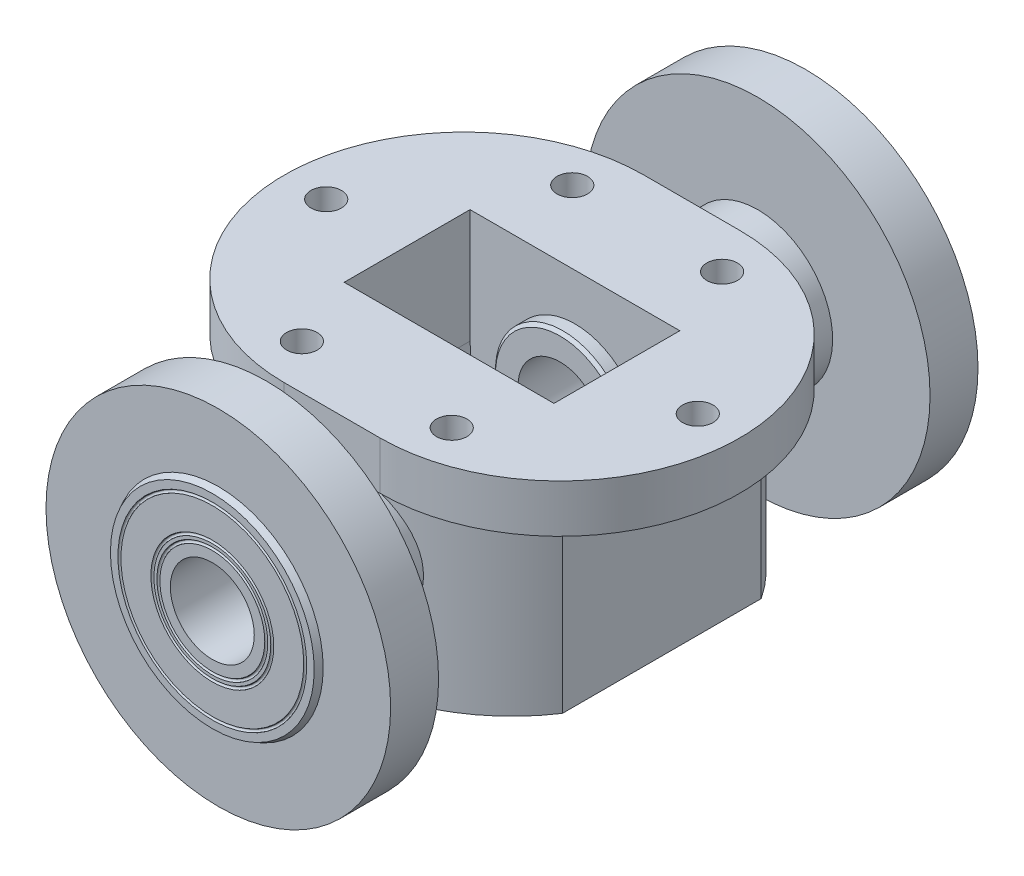
SolidWorks part; units mm, degrees
ref_plane "前视基准面" through (0, 0, 0) normal (0, 0, 1) x (1, 0, 0)
ref_plane "上视基准面" through (0, 0, 0) normal (0, 1, 0) x (1, 0, 0)
ref_plane "右视基准面" through (0, 0, 0) normal (1, 0, 0) x (0, 0, -1)
sketch "草图1" plane through (0, 0, 0) normal (0, 0, 1) x (1, 0, 0)
  circle A0 centre (0, 0) radius 57.5
  dimension "D1" = 115
extrude "凸台-拉伸1" add sketch "草图1" along normal blind 16
sketch "草图2" plane through (0, 0, 16) normal (0, 0, 1) x (1, 0, 0)
  circle A0 centre (0, 0) radius 35
  dimension "D1" = 70
ref_plane "基准面1" through (0, 0, 18) normal (0, 0, 1) x (1, 0, 0)
sketch "草图3" plane through (0, 0, 18) normal (0, 0, 1) x (1, 0, 0)
  circle A0 centre (0, 0) radius 34
  dimension "D1" = 68
loft "放样1" add profiles "草图2", "草图3"
ref_plane "基准面2" through (0, 0, -82) normal (0, 0, 1) x (1, 0, 0)
sketch "草图4" plane through (0, 0, 0) normal (0, 0, -1) x (-1, 0, 0)
  circle A0 centre (0, 0) radius 25
  dimension "D1" = 50
extrude "凸台-拉伸2" add sketch "草图4" along normal blind 164
sketch "草图5" plane through (0, 0, -164) normal (0, 0, -1) x (-1, 0, 0)
  circle A1 centre (0, 0) radius 57.5
  circle A2 centre (0, 0) radius 57.5
  dimension "D1" = 0
extrude "凸台-拉伸3" add sketch "草图5" along normal blind 16
sketch "草图6" plane through (0, 0, -180) normal (0, 0, -1) x (-1, 0, 0)
  circle A0 centre (0, 0) radius 35
  dimension "D1" = 70
ref_plane "基准面3" through (0, 0, -182) normal (0, 0, -1) x (-1, 0, 0)
sketch "草图7" plane through (0, 0, -182) normal (0, 0, -1) x (-1, 0, 0)
  circle A0 centre (0, 0) radius 34
  dimension "D1" = 68
loft "放样2" add profiles "草图6", "草图7"
sketch "草图8" plane through (0, 0, 0) normal (0, 1, 0) x (1, 0, 0)
  line L0 (0, -18) -> (0, 182) construction
  line L5 (-34, -18) -> (34, -18) construction
  line L6 (34, 182) -> (-34, 182) construction
  circle A0 centre (0, 82) radius 50
  dimension "D1" = 100
extrude "凸台-拉伸4" add sketch "草图8" along normal mid plane 76
sketch "草图10" plane through (0, 38, 0) normal (0, 1, 0) x (1, 0, 0)
  circle A0 centre (0, 82) radius 19
  circle A1 centre (0, 82) radius 50 construction
  dimension "D1" = 38
extrude "切除-拉伸1" cut sketch "草图10" against normal through all both and the other way through all
sketch "草图11" plane through (0, 38, 0) normal (0, 1, 0) x (1, 0, 0)
  line L0 (-16, 82) -> (16, 82) construction
  line L2 (-16, 142) -> (16, 142)
  line L3 (-16, 22) -> (16, 22)
  arc A0 (-16, 142) -> (-16, 22) centre (-16, 82) ccw
  arc A1 (16, 22) -> (16, 142) centre (16, 82) ccw
  circle A2 centre (0, 82) radius 19 construction
  circle A3 centre (0, 82) radius 19
  point P5 (0, 82)
  circle M8 centre (0, 82) radius 50
  dimension "D2" = 60
  dimension "D1" = 32
extrude "凸台-拉伸5" add sketch "草图11" against normal blind 16 contours L3 A1 L2 A0 M8
sketch "草图12" plane through (0, 38, 0) normal (0, 1, 0) x (1, 0, 0)
  line L0 (16, 128) -> (16, 36) construction
  line L2 (-16, 22) -> (16, 22)
  line L3 (16, 142) -> (-16, 142)
  line L4 (-16, 22) -> (16, 22)
  line L5 (16, 142) -> (-16, 142)
  line L7 (0, -63.25) -> (0, 63.25) construction
  line L8 (-16, 128) -> (-16, 36) construction
  line L9 (-25, 82) -> (25, 82) construction
  line L10 (25, 127.111) -> (25, 36.889) construction
  line L11 (-25, 127.111) -> (-25, 36.889) construction
  line L18 (62, 82) -> (-62, 82) construction
  arc A0 (16, 128) -> (16, 36) centre (16, 82) cw construction
  arc A2 (16, 22) -> (16, 142) centre (16, 82) ccw
  arc A3 (-16, 142) -> (-16, 22) centre (-16, 82) ccw
  arc A4 (16, 22) -> (16, 142) centre (16, 82) ccw
  arc A5 (-16, 142) -> (-16, 22) centre (-16, 82) ccw
  arc A6 (-16, 128) -> (-16, 36) centre (-16, 82) ccw construction
  point P22 (0, 82)
  point P39 (-62, 82)
  dimension "D2" = 46
  dimension "D3" = 25
  dimension "D1" = 0
hole_wizard "M12 螺纹孔1" positions "3D草图1" profile "草图13" tap size "M12" standard "GB"
sketch3d "3D草图1"
  point P0 (-62, 38, -82)
  point P3 (-25, 38, -127.111)
  point P6 (-25, 38, -36.889)
  point P9 (25, 38, -127.111)
  point P12 (25, 38, -36.889)
  point P15 (62, 38, -82)
sketch "草图13" plane through (-62, 38, -82) normal (1, 0, 0) x (0, 0, 1)
  line L0 (0, 0) -> (0, 15.0644)
  line L1 (0, 15.0644) -> (5.1, 12)
  line L2 (5.1, 12) -> (5.1, 0)
  line L5 (5.1, 0) -> (0, 0)
  line L10 (0, 15.0644) -> (-5.1, 12) construction
  line L11 (0, -6.35) -> (0, 107.95) construction
  dimension "螺纹孔钻头直径" = 10.2
  dimension "螺纹孔钻头深度" = 12
  dimension "导头角度" = 118
cosmetic thread "孔螺蚊线1" parameters "D1"=12, "D2"=12
cosmetic thread "孔螺蚊线2" parameters "D1"=12, "D2"=12
cosmetic thread "孔螺蚊线3" parameters "D1"=12, "D2"=12
cosmetic thread "孔螺蚊线4" parameters "D1"=12, "D2"=12
cosmetic thread "孔螺蚊线5" parameters "D1"=12, "D2"=12
cosmetic thread "孔螺蚊线6" parameters "D1"=12, "D2"=12
sketch "草图14" plane through (0, 0, -182) normal (0, 0, -1) x (-1, 0, 0)
  circle A0 centre (0, 0) radius 14
  dimension "D1" = 28
extrude "切除-拉伸2" cut sketch "草图14" against normal through all both and the other way through all
sketch "草图15" plane through (0, 0, -82) normal (0, 0, 1) x (1, 0, 0)
  line L0 (35, 0) -> (35, 38)
  line L1 (35, 38) -> (76, 38) construction
  line L2 (76, 38) -> (16, 38) construction
  line L3 (76, 22) -> (76, 38) construction
  line L4 (0, 0) -> (0, 92.227) construction
  line L5 (-35, 0) -> (-35, 38)
  line L6 (-35, 38) -> (35, 38)
  circle A0 centre (0, 0) radius 35
  dimension "D1" = 70
extrude "切除-拉伸3" cut sketch "草图15" against normal mid plane 42 contours A0 | A0 L0 L6 L5
sketch "草图16" plane through (0, 0, -61) normal (0, 0, -1) x (-1, 0, 0)
  circle A0 centre (0, 0) radius 22.5
  circle A1 centre (0, 0) radius 14 construction
  circle A2 centre (0, 0) radius 14
  dimension "D1" = 45
extrude "凸台-拉伸6" add sketch "草图16" along normal blind 5
mirror "镜向3" about plane through (0, 0, -82) normal (0, 0, 1) of "凸台-拉伸6"
chamfer "倒角1" distance 1 angle 45 2 edges at (-22.5, 0, -66) (-22.5, 0, -98)
sketch "草图17" plane through (0, 0, 18) normal (0, 0, 1) x (1, 0, 0)
  circle A0 centre (0, 0) radius 18
  circle A1 centre (0, 0) radius 20
  circle A2 centre (0, 0) radius 31
  dimension "D1" = 36
  dimension "D2" = 40
  dimension "D3" = 62
sweep "切除-扫描1" cut path "草图17" circular profile diameter 1 parameters "D3"=1
sketch "草图26" plane through (0, 0, 18) normal (0, 0, 1) x (1, 0, 0)
  circle A0 centre (0, 0) radius 20 construction
  circle A1 centre (0, 0) radius 20
sweep "切除-扫描2" cut path "草图26" circular profile diameter 1 parameters "D3"=1
sketch "草图31" plane through (0, 0, 18) normal (0, 0, 1) x (1, 0, 0)
  circle A0 centre (0, 0) radius 31 construction
  circle A1 centre (0, 0) radius 31
sweep "切除-扫描3" cut path "草图31" circular profile diameter 1 parameters "D3"=1
sketch "草图36" plane through (0, -38, 0) normal (0, -1, 0) x (1, 0, 0)
  circle A0 centre (0, -82) radius 60
  arc A1 (11.8743, -130.5695) -> (11.8743, -33.4305) centre (0, -82) ccw construction
  arc A2 (11.8743, -130.5695) -> (11.8743, -33.4305) centre (0, -82) ccw
  circle A4 centre (0, -82) radius 50 construction
  circle A5 centre (0, -82) radius 50
  circle M4 centre (0, -82) radius 50
  dimension "D1" = 120
extrude "凸台-拉伸7" add sketch "草图36" against normal up to next contours A0 M4
sketch "草图37" plane through (0, -38, 0) normal (0, -1, 0) x (1, 0, 0)
  line L1 (-50, -32) -> (50, -32)
  line L2 (-50, -32) -> (-50, -132)
  line L3 (-50, -132) -> (50, -132)
  line L4 (50, -32) -> (50, -132)
  line L5 (-50, -32) -> (50, -132) construction
  line L6 (-50, -132) -> (50, -32) construction
  circle A1 centre (0, -82) radius 60
  circle A2 centre (0, -82) radius 60
  point P0 (0, -82)
  circle M7 centre (0, -82) radius 60
  dimension "D1" = 100
  dimension "D2" = 0
extrude "切除-拉伸4" cut sketch "草图37" against normal up to surface (60 mm away) contours L4 M7 | L2 M7 up to face at (31.2705, 22, -82)
mirror "镜向4" about plane through (0, 0, -82) normal (0, 0, 1) of "切除-扫描3", "切除-扫描2", "切除-扫描1"
